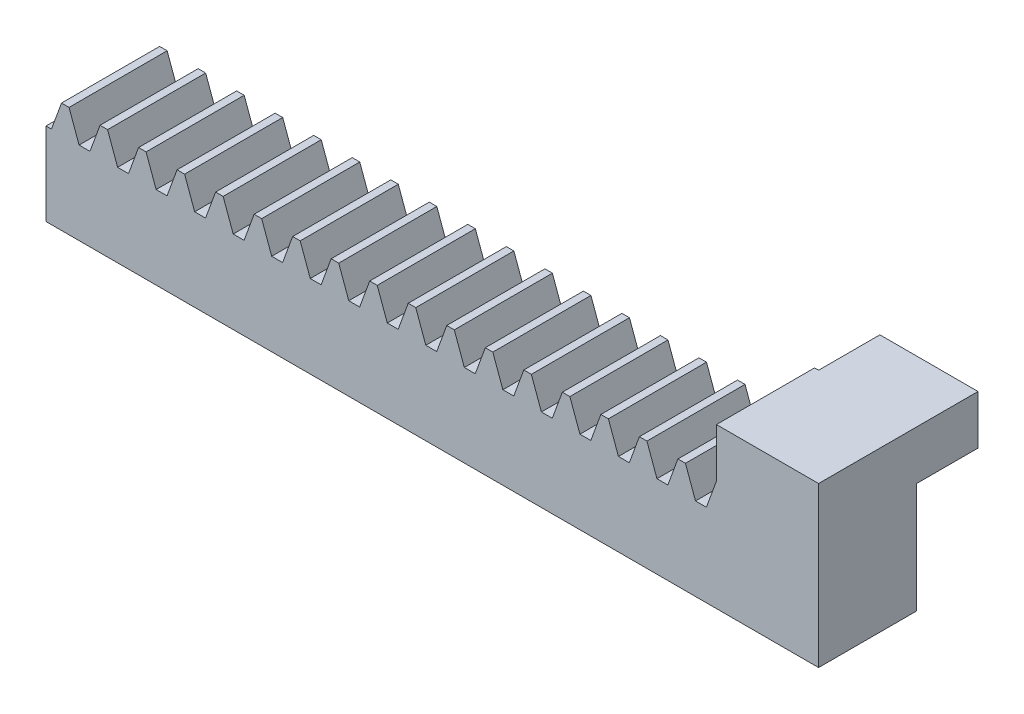
SolidWorks part; units mm, degrees
extrude "Blank" add sketch "BlankSke" against normal blind 8
sketch "BlankSke" plane through (0, 0, 0) normal (0, 0, 1) x (1, 0, 0)
  line L1 (0, 0) -> (55, 0)
  line L2 (0, 0) -> (0, 9)
  line L3 (0, 9) -> (55, 9)
  line L4 (55, 0) -> (55, 9)
  dimension "Length" = 55
  dimension "Blank_height" = 9
ref_plane "Plane1" through (0, 0, 0) normal (0, 0, 1) x (1, 0, 0)
ref_plane "Plane2" through (0, 0, 0) normal (0, 1, 0) x (1, 0, 0)
ref_plane "Plane3" through (0, 0, 0) normal (1, 0, 0) x (0, 0, -1)
other "Configuration Table"
sketch "HoldingSke" plane through (0, 0, 0) normal (0, 1, 0) x (1, 0, 0)
  line L0 (0, 0) -> (0.1392, 0.9903)
  line L1 (-15, 0) -> (100, 0) construction
  line L2 (0, 0) -> (-2.1039, 2.3779)
  line L3 (0, 0) -> (-11.863, 4.5341)
  line L4 (0, 0) -> (8.1655, 2.8116)
  line L5 (0, 0) -> (-23.7986, -8.8762)
  line L6 (0, 0) -> (-10.5278, -7.1032)
  line L9 (-71.009, 38.7566) -> (-19.3259, 57.5677)
  line L10 (-76.2, 3.3779) -> (-68.2, 3.3779)
  line L11 (0, 0) -> (-8, 0)
  line L12 (-76.2, 101.6) -> (-76.162, 101.6)
  line L13 (24.9733, 27.94) -> (52.9518, 28.4284)
  line L14 (24.9733, 27.94) -> (24.9743, 27.94)
  line L15 (24.9733, 27.94) -> (100.4006, 29.5858)
  circle A0 centre (0, 0) radius 19.05
  circle A1 centre (0, 0) radius 4
  circle A2 centre (0, 0) radius 12.7
  dimension "MPH" = 8
  dimension "Diameter" = 38.1
  dimension "Num_teeth" = 19
  dimension "Pitch" = 1
  dimension "Show_teeth" = 998
  dimension "Thickness" = 12.7
  dimension "Ap" = 20
  dimension "Pitch_height" = 8
  dimension "Width" = 8
  dimension "Backlash" = 0.038
  dimension "Addendum_fac" = 1
  dimension "Dedendum_fac" = 1.25
  dimension "Clearance_fac" = 0.25
  dimension "Dedendum_add" = 0.001
  dimension "Length" = 55
  dimension "Module" = 1
sketch "TooCutSkeIll" plane through (0, 0, 0) normal (0, 0, 1) x (1, 0, 0)
  line L0 (-1.2538, 8.9737) -> (-0.5045, 6.9152)
  line L1 (-0.2687, 6.75) -> (0.2687, 6.75)
  line L2 (0.5045, 6.9152) -> (1.2538, 8.9737)
  line L3 (55, 9) -> (0, 9) construction
  line L4 (0, 0) -> (0, 64.897) construction
  line L5 (-13.208, 8) -> (12.954, 8) construction
  line L6 (0, 0) -> (55, 0) construction
  line L7 (0.8994, 8) -> (0.8994, 48.7463) construction
  line L8 (-0.8994, 8) -> (-0.8994, 48.7463) construction
  line L9 (1.2914, 9) -> (1.2914, 9.0254)
  line L10 (-1.2914, 9) -> (-1.2914, 9.0254)
  line L11 (-1.2914, 9.0254) -> (1.2914, 9.0254)
  arc A0 (0.2687, 6.75) -> (0.5045, 6.9152) centre (0.2687, 7.001) ccw
  arc A1 (-0.5045, 6.9152) -> (-0.2687, 6.75) centre (-0.2687, 7.001) ccw
  arc A2 (1.2914, 9) -> (1.2538, 8.9737) centre (1.2914, 8.96) ccw
  arc A3 (-1.2538, 8.9737) -> (-1.2914, 9) centre (-1.2914, 8.96) ccw
  dimension "Pitch_height" = 8
  dimension "Addendum_plus" = 1.0254
  dimension "Pressure_angle" = 20
  dimension "Gap_width" = 1.7988
  dimension "Dedendum" = 1.25
extrude "ToothCutIll" [suppressed] cut sketch "TooCutSkeIll" against normal through all
sketch "TooCutSkeSim" plane through (0, 0, 0) normal (0, 0, 1) x (1, 0, 0)
  line L0 (0.4444, 6.75) -> (-0.4444, 6.75)
  line L1 (1.2726, 9.0254) -> (0.4444, 6.75)
  line L2 (0, 17.4625) -> (0, 53.467) construction
  line L3 (1.2726, 9.0254) -> (-1.2726, 9.0254)
  line L6 (-1.2726, 9.0254) -> (-0.4444, 6.75)
  line L9 (-0.8994, 8) -> (0.8994, 8) construction
  line L10 (0, 0) -> (55, 0) construction
  line L11 (0.8994, 8) -> (0.8994, 53.467) construction
  line L12 (-0.8994, 8) -> (-0.8994, 53.467) construction
  dimension "Pitch_height" = 8
  dimension "Addendum_plus" = 1.0254
  dimension "Pressure_angle" = 20
  dimension "Gap_width" = 1.7988
  dimension "Dedendum" = 1.25
extrude "ToothCutSim" cut sketch "TooCutSkeSim" against normal through all
pattern_linear "TeethCuts" count 18 spacing 3.1416 along (1, 0, 0) of "ToothCutIll", "ToothCutSim"
sketch "Sketch1" plane through (55, 0, 0) normal (1, 0, 0) x (0, 0, -1)
  line L4 (0, 9) -> (0, 0)
  line L5 (0, 0) -> (8, 0)
  line L6 (8, 0) -> (8, 9)
  line L7 (8, 9) -> (0, 9)
  line L8 (0, 9) -> (0, 0)
  line L9 (0, 0) -> (8, 0)
  line L10 (8, 0) -> (8, 9)
  line L11 (8, 9) -> (0, 9)
  dimension "D1" = 0
extrude "Boss-Extrude1" add sketch "Sketch1" along normal blind 8
sketch "Sketch2" plane through (0, 9, 0) normal (0, 1, 0) x (1, 0, 0)
  line L4 (54.6704, 8) -> (54.6704, 0)
  line L5 (54.6704, 0) -> (63, 0)
  line L6 (63, 0) -> (63, 8)
  line L7 (63, 8) -> (54.6704, 8)
  line L8 (54.6704, 8) -> (54.6704, 0)
  line L9 (54.6704, 0) -> (63, 0)
  line L10 (63, 0) -> (63, 8)
  line L11 (63, 8) -> (54.6704, 8)
  dimension "D1" = 0
extrude "Boss-Extrude2" add sketch "Sketch2" along normal blind 4
sketch "Sketch3" plane through (0, 0, -8) normal (0, 0, -1) x (-1, 0, 0)
  line L11 (-63, 13) -> (-55, 13)
  line L12 (-63, 13) -> (-63, 9)
  line L13 (-63, 9) -> (-55, 9)
  line L14 (-55, 13) -> (-55, 9)
  dimension "D1" = 4
  dimension "D2" = 8
extrude "Boss-Extrude3" add sketch "Sketch3" along normal blind 5
equation "' \"Module@HoldingSke\" = 6.35"
equation "' \"Num_teeth@HoldingSke\" = 12"
equation "' \"Ap@HoldingSke\" =  20"
equation "' \"Ap@HoldingSke\" = 20"
equation "' \"Width@HoldingSke\" = 0.25 * 25.4"
equation "' \"Show_teeth@HoldingSke\" = 500"
equation "' \"Backlash@HoldingSke\" = 0.009 * 25.4"
equation "' \"Addendum_fac@HoldingSke\" = 1.0"
equation "' \"Dedendum_fac@HoldingSke\" = 1.25"
equation "' \"Dedendum_add@HoldingSke\" = 0.00005 * 25.4"
equation "' \"Clearance_fac@HoldingSke\" = 0.25"
equation "' \"Pitch_height@HoldingSke\" = 1 * 25.4"
equation "' \"Length@HoldingSke\" = 4.71 * 25.4"
equation "\"Pitch@HoldingSke\" = 1 / \"Module@HoldingSke\""
equation "\"MPH@HoldingSke\" = \"Dedendum_fac@HoldingSke\" / \"Pitch@HoldingSke\" + 2 * \"Dedendum_add@HoldingSke\" + 0.002 * 25.4"
equation "\"MPH@HoldingSke\" = ((sgn( \"MPH@HoldingSke\" - \"Pitch_height@HoldingSke\")+1)*( \"MPH@HoldingSke\" - \"Pitch_height@HoldingSke\"))/2 + \"Pitch_height@HoldingSke\""
equation "\"Blank_height@BlankSke\" = \"Pitch_height@HoldingSke\" + \"Addendum_fac@HoldingSke\"  / \"Pitch@HoldingSke\" "
equation "\"Length@BlankSke\" =  \"Length@HoldingSke\""
equation "\"Face_width@Blank\" = \"Width@HoldingSke\""
equation "\"Pressure_angle@TooCutSkeIll\" = \"Ap@HoldingSke\""
equation "\"Addendum_plus@TooCutSkeIll\" =  \"Addendum_fac@HoldingSke\"  / \"Pitch@HoldingSke\" + 0.001 *25.4"
equation "\"Dedendum@TooCutSkeIll\" = \"Dedendum_fac@HoldingSke\"  / \"Pitch@HoldingSke\""
equation "\"Pitch_height@TooCutSkeIll\" =  \"MPH@HoldingSke\""
equation "\"Gap_width@TooCutSkeIll\" = 3.14159265 / 2 / \"Pitch@HoldingSke\" + 6 * \"Backlash@HoldingSke\""
equation "\"Pressure_angle@TooCutSkeSim\" = \"Ap@HoldingSke\""
equation "\"Addendum_plus@TooCutSkeSim\" =  \"Addendum_fac@HoldingSke\"  / \"Pitch@HoldingSke\" + 0.001 * 25.4"
equation "\"Dedendum@TooCutSkeSim\" = \"Dedendum_fac@HoldingSke\"  / \"Pitch@HoldingSke\""
equation "\"Pitch_height@TooCutSkeSim\" =  \"MPH@HoldingSke\""
equation "\"Gap_width@TooCutSkeSim\" = 3.14159265 / 2 / \"Pitch@HoldingSke\" + 6 * \"Backlash@HoldingSke\""
equation "\"Root_fillet@TooCutSkeIll\" = \"Clearance_fac@HoldingSke\" / \"Pitch@HoldingSke\" + \"Dedendum_add@HoldingSke\""
equation "\"Break_rad@TooCutSkeIll\" = 0.02 / \"Pitch@HoldingSke\" * 2"
equation "\"Linear_pitch@TeethCuts\" = 3.14159265 / \"Pitch@HoldingSke\""
equation "\"Num_teeth@HoldingSke\" = int( ( \"Length@HoldingSke\" + 0 ) / (3.14159265 / \"Pitch@HoldingSke\")) + 0.9999  + 1"
equation " \"Num_teeth@TeethCuts\" = int( \"Show_teeth@HoldingSke\" ) + 1"
equation " \"Num_teeth@TeethCuts\" = ((sgn( \"Num_teeth@TeethCuts\" - \"Num_teeth@HoldingSke\" )-1)*( \"Num_teeth@TeethCuts\" - \"Num_teeth@HoldingSke\" ))/-2+ \"Num_teeth@HoldingSke\""
equation " \"Num_teeth@TeethCuts\" = ((sgn( \"Num_teeth@TeethCuts\" - 2.0)+1)*( \"Num_teeth@TeethCuts\" - 2.0))/2 +2.0"
